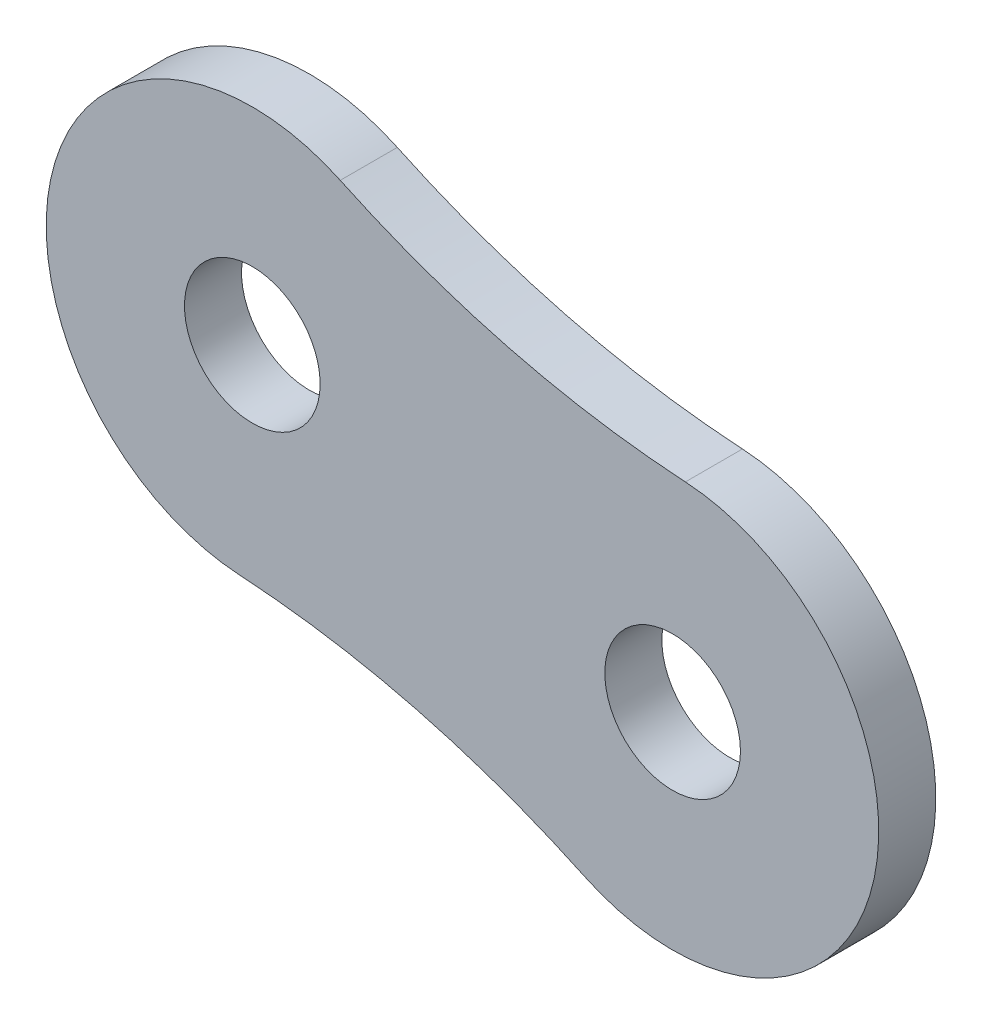
SolidWorks part; units mm, degrees
ref_plane "前视基准面" through (0, 0, 0) normal (0, 0, 1) x (1, 0, 0)
ref_plane "上视基准面" through (0, 0, 0) normal (0, 1, 0) x (1, 0, 0)
ref_plane "右视基准面" through (0, 0, 0) normal (1, 0, 0) x (0, 0, -1)
sketch "草图1" plane through (0, 0, 0) normal (0, 0, 1) x (1, 0, 0)
  line L0 (-12.7, 0) -> (12.7, 0) construction
  line L1 (0, 10.8585) -> (0, -10.8585) construction
  line L2 (12.7, 0) -> (35.31, 0) construction
  line L3 (35.31, 0) -> (51.06, 0) construction
  circle A0 centre (-12.7, 0) radius 12.065
  circle A1 centre (12.7, 0) radius 12.065
  circle A2 centre (0, 66.2389) radius 55.3804
  circle A3 centre (0, -66.2389) radius 55.3804
  circle A4 centre (-12.7, 0) radius 7.94
  circle A5 centre (12.7, 0) radius 7.94
  circle A6 centre (-12.7, 0) radius 3.97
  circle A7 centre (12.7, 0) radius 3.97
  point P16 (75.4, 0)
  point P18 (41.99, 0)
  point P19 (14.7, 0)
  dimension "h2" = 24.13
  dimension "d1" = 15.88
  dimension "d2" = 7.94
  dimension "p" = 25.4
  dimension "h3" = 21.717
  dimension "b2" = 22.61
  dimension "b1" = 15.75
  dimension "b5" = 62.7
  dimension "P1" = 29.29
  dimension "z" = 2
sketch "草图2" plane through (0, 0, 0) normal (0, 0, 1) x (1, 0, 0)
  circle A0 centre (12.7, 0) radius 7.94 construction
  circle A1 centre (-12.7, 0) radius 7.94 construction
  circle A2 centre (12.7, 0) radius 7.94
  circle A3 centre (-12.7, 0) radius 7.94
extrude "拉伸1" add sketch "草图2" along normal mid plane 15.75
sketch "草图3" plane through (0, 0, 7.875) normal (0, 0, 1) x (1, 0, 0)
  circle A0 centre (-12.7, 0) radius 12.065 construction
  arc A1 (-10.4282, 11.8492) -> (-10.4282, -11.8492) centre (-12.7, 0) ccw
  circle A2 centre (12.7, 0) radius 12.065 construction
  arc A3 (10.4282, -11.8492) -> (10.4282, 11.8492) centre (12.7, 0) ccw
  circle A4 centre (0, 66.2389) radius 55.3804 construction
  arc A5 (-10.4282, 11.8492) -> (10.4282, 11.8492) centre (0, 66.2389) ccw
  circle A6 centre (0, -66.2389) radius 55.3804 construction
  arc A7 (10.4282, -11.8492) -> (-10.4282, -11.8492) centre (0, -66.2389) ccw
extrude "拉伸2" add sketch "草图3" along normal blind 3.43
sketch "草图5" plane through (0, 0, 0) normal (0, 0, 1) x (1, 0, 0)
  line L0 (12.7, 0) -> (37.302, -6.3167) construction
  line L1 (-12.7, 0) -> (12.7, 0) construction
  line L2 (-12.7, 0) -> (-776.8532, -96.535)
  line L4 (0, -100.5309) -> (-768.1907, -165.1058) construction
  line L5 (37.302, -6.3167) -> (59.5602, -18.5533) construction
  arc A0 (30.9597, -197.0153) -> (-12.7, 0) centre (0, -100.5309) ccw
  arc A1 (-776.8532, -96.535) -> (-783.5035, -232.504) centre (-768.1907, -165.1058) ccw
  arc A2 (-783.5035, -232.504) -> (30.9597, -197.0153) centre (-441.1553, 1274.3085) ccw
  dimension "R2" = 202.6597
  dimension "R1" = 138.2317
  dimension "a" = 770.9
  dimension "La" = 770.2266
  dimension "L2" = 299.6078
  dimension "L" = 825
  dimension "L1" = 193.0074
sketch "草图6" plane through (0, 0, 11.305) normal (0, 0, 1) x (1, 0, 0)
  arc A0 (32.1548, -17.2286) -> (38.0483, 5.7252) centre (37.302, -6.3167) ccw
  circle A1 centre (12.7, 0) radius 12.065 construction
  arc A2 (17.8472, 10.9119) -> (11.9537, -12.0419) centre (12.7, 0) ccw
  arc A3 (17.8472, 10.9119) -> (38.0483, 5.7252) centre (41.4739, 60.9995) ccw
  arc A4 (11.9537, -12.0419) -> (32.1548, -17.2286) centre (8.5281, -67.3162) cw
  circle A5 centre (0, 66.2389) radius 55.3804 construction
  circle A6 centre (0, -66.2389) radius 55.3804 construction
  circle A7 centre (12.7, 0) radius 3.97 construction
  circle A8 centre (12.7, 0) radius 3.97
  circle A9 centre (37.302, -6.3167) radius 3.97
extrude "拉伸4" add sketch "草图6" along normal blind 3.34 separate body
delete or keep bodies "实体-删除1" type delete bodies bodies 103
equation "\"D1@拉伸1\" = \"b1@草图1\""
equation "\"D1@拉伸2\" = (  \"b2@草图1\" - \"D1@拉伸1\" )  / 2"
equation "\"h3@草图1\" = \"h2@草图1\" * 0.9"
equation "\"D1@拉伸4\" = (\"P1@草图1\"-\"b2@草图1\")/2"
